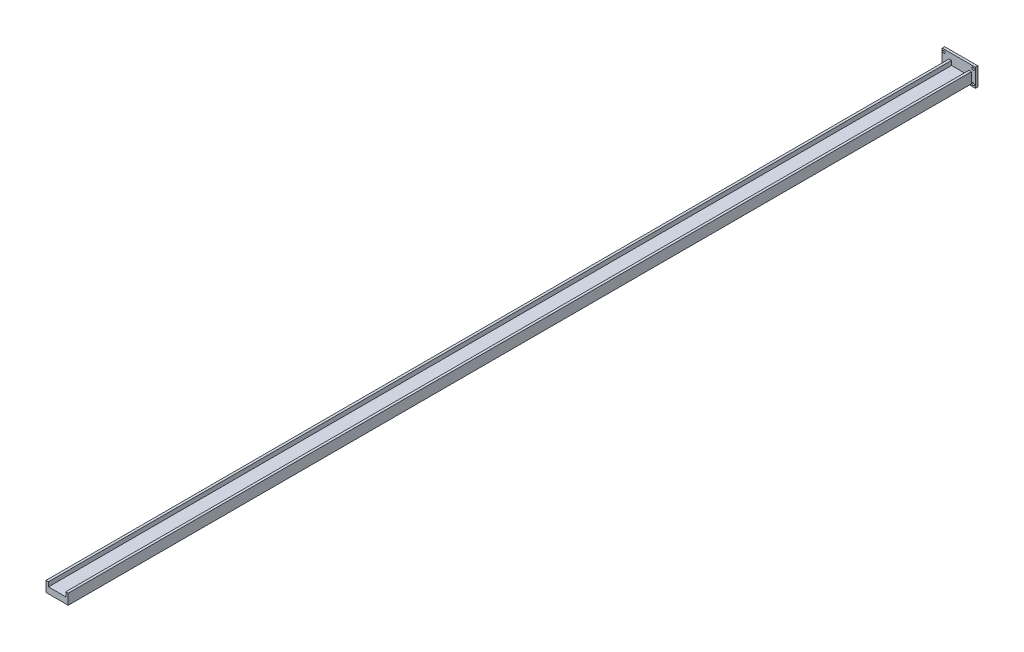
SolidWorks part; units mm, degrees
ref_plane "Front Plane" through (0, 0, 0) normal (0, 0, 1) x (1, 0, 0)
ref_plane "Top Plane" through (0, 0, 0) normal (0, 1, 0) x (1, 0, 0)
ref_plane "Right Plane" through (0, 0, 0) normal (1, 0, 0) x (0, 0, -1)
sketch "Sketch1" plane through (0, 0, 0) normal (0, 0, 1) x (1, 0, 0)
  line L0 (-20.9875, 6.6007) -> (-15.9875, 6.6007)
  line L2 (-15.9875, 6.6007) -> (-15.9875, -2.3588)
  line L3 (-15.9875, -2.3588) -> (19.0125, -2.3588)
  line L4 (19.0125, 6.6007) -> (19.0125, -2.3588)
  line L5 (19.0125, 6.6007) -> (24.0125, 6.6007)
  line L8 (-20.9875, 6.6007) -> (-20.9875, -14.7268)
  line L9 (-20.9875, -14.7268) -> (24.0125, -14.7268)
  line L10 (24.0125, 6.6007) -> (24.0125, -14.7268)
  point P0 (0, 0)
  point P6 (0, 0)
  dimension "D1" = 35
  dimension "D2" = 45
  dimension "D3" = 5
extrude "Boss-Extrude1" add sketch "Sketch1" along normal blind 1828
sketch "Sketch2" plane through (0, 0, 0) normal (0, 0, -1) x (-1, 0, 0)
  line L1 (-32.5972, 18.7245) -> (34.7955, 18.7245)
  line L2 (-32.5972, 18.7245) -> (-32.5972, -18.2161)
  line L3 (-32.5972, -18.2161) -> (34.7955, -18.2161)
  line L4 (34.7955, 18.7245) -> (34.7955, -18.2161)
  circle A0 centre (-27.5972, 13.7245) radius 2.5
  circle A1 centre (31.5653, 13.7245) radius 2.5
  circle A2 centre (31.4144, -13.2161) radius 2.5
  circle A3 centre (-27.7481, -13.2161) radius 2.5
  point P0 (0, 0)
  point P8 (0, 0)
  dimension "D1" = 5
  dimension "D2" = 5
  dimension "D3" = 5
  dimension "D6" = 5
  dimension "D7" = 4.8491
  dimension "D4" = 2
  dimension "D5" = 2
extrude "Boss-Extrude2" add sketch "Sketch2" along normal blind 5
